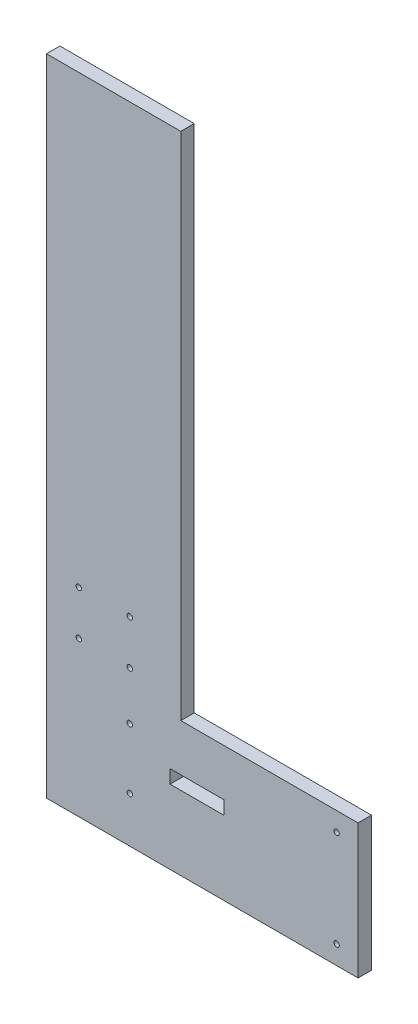
SolidWorks part; units mm, degrees
ref_plane "Front Plane" through (0, 0, 0) normal (0, 0, 1) x (1, 0, 0)
ref_plane "Top Plane" through (0, 0, 0) normal (0, 1, 0) x (1, 0, 0)
ref_plane "Right Plane" through (0, 0, 0) normal (1, 0, 0) x (0, 0, -1)
sketch "Sketch1" plane through (0, 0, 0) normal (0, 0, 1) x (1, 0, 0)
  line L0 (0, 150) -> (180, 150) construction
  line L1 (0, 0) -> (180, 0)
  line L2 (0, 0) -> (0, 300)
  line L3 (0, 300) -> (180, 300) construction
  line L4 (180, 0) -> (180, 300)
  line L5 (0, 300) -> (50, 300)
  line L6 (50, 300) -> (50, 150)
  line L7 (-66, 110) -> (0, 60) construction
  line L8 (0, 110) -> (-66, 110)
  line L9 (0, 110) -> (0, 60)
  line L10 (0, 60) -> (-66, 60)
  line L11 (-66, 110) -> (-66, 60)
  line L12 (0, 110) -> (-66, 60) construction
  line L13 (-33, 85) -> (-66, 85) construction
  line L14 (90, 150) -> (90, 0) construction
  line L15 (180, 110) -> (246, 110)
  line L16 (180, 110) -> (246, 60) construction
  line L17 (246, 110) -> (180, 60) construction
  line L18 (180, 60) -> (246, 60)
  line L19 (213, 85) -> (246, 85) construction
  line L20 (246, 110) -> (246, 60)
  line L21 (11, 117.5) -> (46, 117.5) construction
  line L22 (50, 150) -> (85, 150) construction
  line L23 (50, 150) -> (50, 110) construction
  line L24 (50, 110) -> (85, 110) construction
  line L25 (85, 150) -> (85, 110) construction
  line L26 (11, 150) -> (46, 150) construction
  line L27 (11, 150) -> (11, 110) construction
  line L28 (11, 110) -> (46, 110) construction
  line L29 (46, 150) -> (46, 110) construction
  line L30 (11, 134) -> (46, 134) construction
  line L31 (19, 150) -> (19, 110) construction
  line L32 (38, 150) -> (38, 110) construction
  line L33 (50, 150) -> (130, 150)
  line L34 (130, 300) -> (130, 150)
  line L35 (180, 300) -> (130, 300)
  circle A0 centre (19, 134) radius 1
  circle A1 centre (38, 134) radius 1
  circle A2 centre (19, 117.5) radius 1
  circle A3 centre (38, 117.5) radius 1
  circle A4 centre (161, 117.5) radius 1
  circle A5 centre (142, 117.5) radius 1
  circle A6 centre (142, 134) radius 1
  circle A7 centre (161, 134) radius 1
  point P7 (90, 150)
  dimension "D17" = 2
  dimension "D18" = 2
  dimension "D19" = 2
  dimension "D20" = 2
  dimension "D1" = 180
  dimension "D2" = 300
  dimension "D3" = 150
  dimension "D4" = 156
  dimension "D5" = 50
  dimension "D6" = 85
  dimension "D7" = 35
  dimension "D8" = 5
  dimension "D9" = 40
  dimension "D10" = 40
  dimension "D11" = 4
  dimension "D12" = 35
  dimension "D13" = 7.5
  dimension "D14" = 24
  dimension "D15" = 8
  dimension "D16" = 8
extrude "Boss-Extrude1" add sketch "Sketch1" along normal blind 5
sketch "Sketch2" plane through (0, 0, 5) normal (0, 0, 1) x (1, 0, 0)
  line L0 (-66, 110) -> (-66, 60) construction
  line L1 (-66, 110) -> (-51, 110) construction
  line L2 (-66, 110) -> (-66, 60) construction
  line L3 (-66, 60) -> (-51, 60) construction
  line L4 (-51, 110) -> (-51, 60) construction
  line L5 (0, 60) -> (-66, 60) construction
  line L6 (-58, 110) -> (-58, 60) construction
  line L7 (90, 150) -> (90, 0) construction
  line L8 (0, 0) -> (180, 0) construction
  line L9 (50, 150) -> (130, 150) construction
  circle A0 centre (-58, 103) radius 1
  circle A1 centre (-58, 67) radius 1
  circle A2 centre (238, 67) radius 1
  circle A3 centre (238, 103) radius 1
  dimension "D4" = 2
  dimension "D5" = 7
  dimension "D7" = 2
  dimension "D1" = 50
  dimension "D2" = 15
  dimension "D3" = 7
  dimension "D6" = 7
extrude "Cut-Extrude1" cut sketch "Sketch2" against normal through all
sketch "Sketch3" plane through (0, 0, 5) normal (0, 0, 1) x (1, 0, 0)
  line L0 (-16, 92.5) -> (4, 87.5) construction
  line L1 (-16, 92.5) -> (4, 92.5)
  line L2 (-16, 92.5) -> (-16, 87.5)
  line L3 (-16, 87.5) -> (4, 87.5) construction
  line L4 (4, 92.5) -> (4, 87.5)
  line L5 (-16, 87.5) -> (4, 92.5) construction
  line L6 (19, 74.5) -> (19, 99.5) construction
  line L7 (-66, 110) -> (-66, 60) construction
  line L8 (0, 110) -> (-66, 110) construction
  line L9 (-16, 74.5) -> (4, 74.5) construction
  line L10 (-16, 87.5) -> (4, 87.5)
  line L11 (-16, 87.5) -> (-16, 37.5) construction
  line L12 (-16, 37.5) -> (4, 37.5) construction
  line L13 (4, 87.5) -> (4, 37.5) construction
  line L14 (4, 74.5) -> (19, 74.5) construction
  line L15 (90, 0) -> (90, 150) construction
  line L16 (0, 0) -> (180, 0) construction
  line L17 (50, 150) -> (130, 150) construction
  line L18 (196, 92.5) -> (196, 87.5)
  line L19 (196, 87.5) -> (176, 87.5)
  line L20 (176, 92.5) -> (176, 87.5)
  line L21 (196, 92.5) -> (176, 92.5)
  circle A0 centre (19, 77) radius 1
  circle A1 centre (19, 99.5) radius 1
  circle A2 centre (161, 77) radius 1
  circle A3 centre (161, 99.5) radius 1
  point P4 (-6, 90)
  dimension "D9" = 2
  dimension "D10" = 2
  dimension "D11" = 5
  dimension "D1" = 60
  dimension "D2" = 20
  dimension "D3" = 20
  dimension "D4" = 5
  dimension "D5" = 50
  dimension "D6" = 13
  dimension "D7" = 15
  dimension "D8" = 25
extrude "Cut-Extrude2" cut sketch "Sketch3" against normal through all
sketch "Sketch4" plane through (0, 0, 5) normal (0, 0, 1) x (1, 0, 0)
  line L0 (180, 60) -> (130, 60)
  line L1 (130, 150) -> (130, 60)
  line L2 (180, 60) -> (198.3212, 8.7539)
  line L3 (198.3212, 8.7539) -> (175.3321, -20.8591)
  line L4 (175.3321, -20.8591) -> (-107.9394, -9.1698)
  line L5 (-107.9394, -9.1698) -> (-51.0513, 321.2487)
  line L6 (-51.0513, 321.2487) -> (65.0628, 311.8973)
  line L7 (65.0628, 311.8973) -> (130, 150)
extrude "Cut-Extrude3" cut sketch "Sketch4" against normal through all
